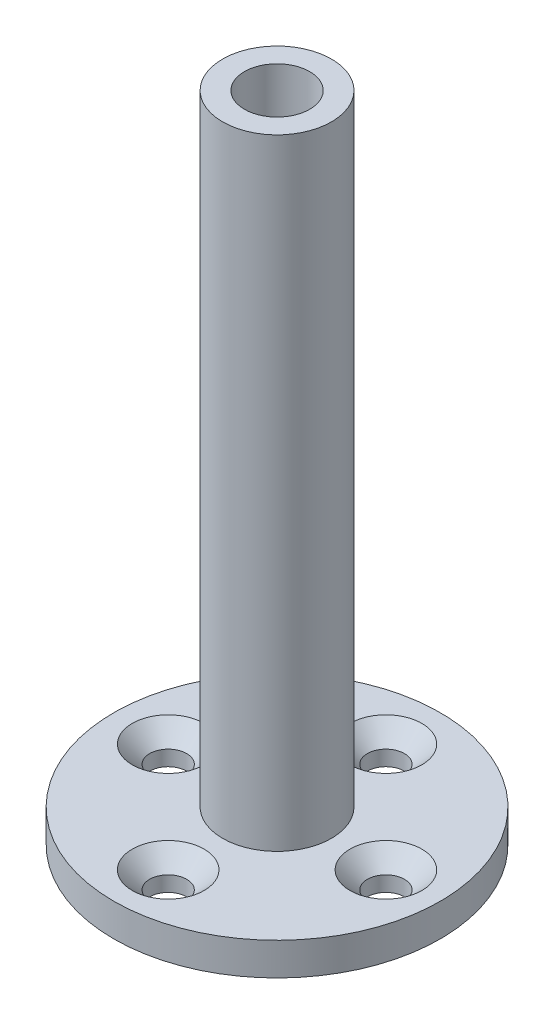
SolidWorks part; units mm, degrees
ref_plane "前视基准面" through (0, 0, 0) normal (0, 0, 1) x (1, 0, 0)
ref_plane "上视基准面" through (0, 0, 0) normal (0, 1, 0) x (1, 0, 0)
ref_plane "右视基准面" through (0, 0, 0) normal (1, 0, 0) x (0, 0, -1)
sketch "草图1" plane through (0, 0, 0) normal (0, 1, 0) x (1, 0, 0)
  circle A0 centre (0, 0) radius 3
  circle A1 centre (0, 0) radius 5
  circle A2 centre (0, 0) radius 10
extrude "凸台-拉伸2" add sketch "草图1" along normal blind 60 contours A1 A0
sketch "草图2" plane through (0, 0, 0) normal (0, 1, 0) x (1, 0, 0)
  circle A0 centre (0, 0) radius 5
  circle A1 centre (0, 0) radius 15
extrude "凸台-拉伸3" add sketch "草图2" along normal blind 3
hole_wizard "打孔尺寸(%根据)开槽沉头木螺钉的类型1" positions "草图3" profile "草图4" countersink size "M3" standard "GB" end condition through all
sketch "草图3" plane through (0, 3, 0) normal (0, 1, 0) x (1, 0, 0)
  point P0 (-10, 0)
  point P2 (0, -10)
  point P4 (10, 0)
  point P6 (0, 10)
sketch "草图4" plane through (-10, 3, 0) normal (1, 0, 0) x (0, 0, 1)
  line L0 (0, 0) -> (0, 3)
  line L1 (0, 3) -> (1.7, 3)
  line L2 (1.7, 3) -> (1.7, 1.6)
  line L3 (1.7, 1.6) -> (3.3, 0)
  line L5 (3.3, 0) -> (0, 0)
  line L6 (-1.7, 1.6) -> (-3.3, 0) construction
  line L11 (0, -6.35) -> (0, 107.95) construction
  dimension "通孔孔直径" = 3.4
  dimension "通孔孔深度" = 3
  dimension "近端锥形沉头孔直径" = 6.6
  dimension "近端锥形沉头孔角度" = 90
